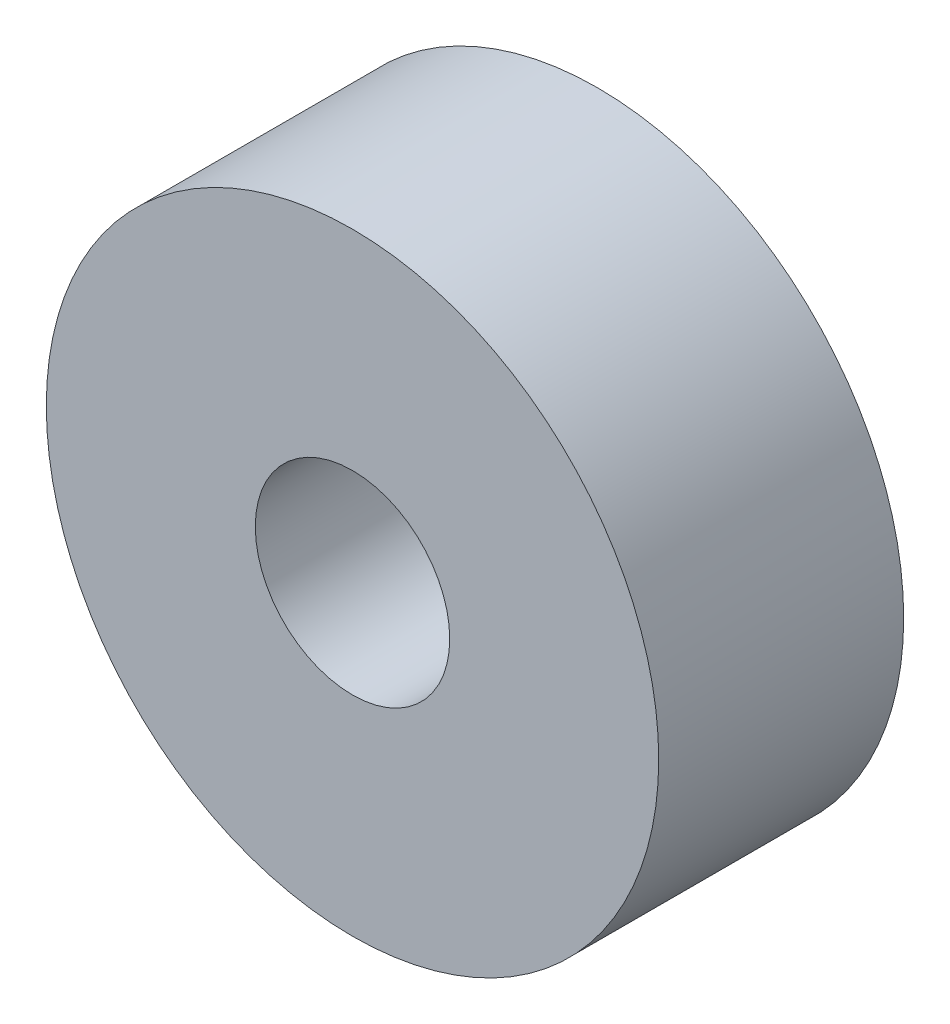
SolidWorks part; units mm, degrees
ref_plane "Front Plane" through (0, 0, 0) normal (0, 0, 1) x (1, 0, 0)
ref_plane "Top Plane" through (0, 0, 0) normal (0, 1, 0) x (1, 0, 0)
ref_plane "Right Plane" through (0, 0, 0) normal (1, 0, 0) x (0, 0, -1)
sketch "Sketch1" plane through (0, 0, 0) normal (0, 0, 1) x (1, 0, 0)
  circle A0 centre (0, 0) radius 5
  circle A1 centre (0, 0) radius 1.5875
extrude "Boss-Extrude1" add sketch "Sketch1" along normal blind 4
